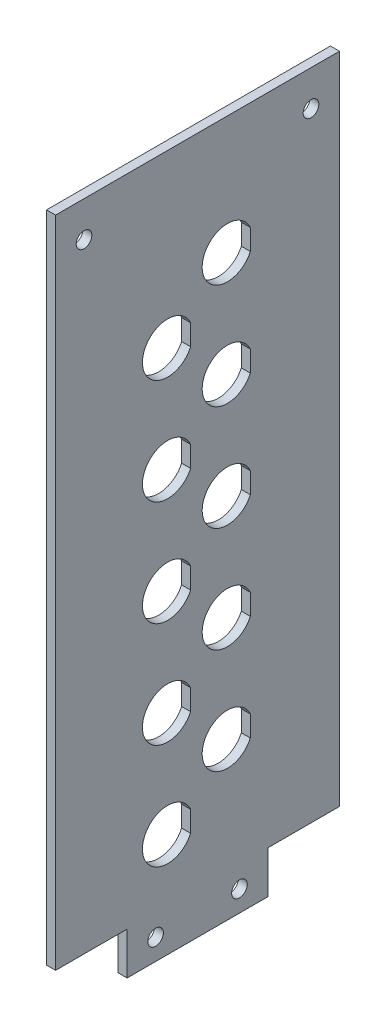
SolidWorks part; units mm, degrees
ref_plane "Front Plane" through (0, 0, 0) normal (1, 0, 0) x (0, 1, 0)
ref_plane "Top Plane" through (0, 0, 0) normal (0, 0, 1) x (0, 1, 0)
ref_plane "Right Plane" through (0, 0, 0) normal (0, 1, 0) x (-1, 0, 0)
sketch "Sketch1" plane through (0, 0, 0) normal (1, 0, 0) x (0, 1, 0)
  line L0 (-129.9, 24.75) -> (-115, 49.9) construction
  line L1 (-115, -49.9) -> (115, -49.9)
  line L2 (-115, -49.9) -> (-115, 49.9)
  line L3 (-115, 49.9) -> (115, 49.9)
  line L4 (115, -49.9) -> (115, 49.9)
  line L5 (-115, -49.9) -> (115, 49.9) construction
  line L6 (-115, 49.9) -> (115, -49.9) construction
  line L7 (-115, 24.75) -> (-129.9, 24.75)
  line L8 (-115, 24.75) -> (-115, -24.75)
  line L9 (-115, -24.75) -> (-129.9, -24.75)
  line L10 (-129.9, 24.75) -> (-129.9, -24.75)
  line L11 (-115, 24.75) -> (-129.9, -24.75) construction
  line L12 (-115, -24.75) -> (-129.9, 24.75) construction
  line L13 (-129.9, -24.75) -> (-115, -49.9) construction
  line L14 (102.5, 39.9) -> (102.5, -39.9) construction
  line L15 (102.5, 0) -> (115, 0) construction
  line L16 (-129.9, 0) -> (-122.5, 0) construction
  line L17 (-122.5, -14.75) -> (-122.5, 14.75) construction
  line L19 (-129.9, 24.75) -> (-135, 24.75) construction
  line L20 (-129.9, 24.75) -> (-129.9, -24.75) construction
  line L21 (-129.9, -24.75) -> (-135, -24.75) construction
  line L22 (-135, 24.75) -> (-135, -24.75) construction
  line L23 (-129.9, 24.75) -> (-135, -24.75) construction
  line L24 (-129.9, -24.75) -> (-135, 24.75) construction
  circle A0 centre (102.5, 39.9) radius 2.75
  circle A1 centre (102.5, -39.9) radius 2.75
  circle A2 centre (-122.5, 14.75) radius 2.75
  circle A3 centre (-122.5, -14.75) radius 2.75
  point P0 (0, 0)
  point P10 (-122.45, 0)
  point P21 (-122.5, 0)
  point P25 (-123.75, 14.75)
  point P27 (-132.45, 0)
  point P28 (-142.7036, -24.4057)
  dimension "D1" = 5.5
  dimension "D2" = 99.8
  dimension "D11" = 5.5
  dimension "D3" = 12.5
  dimension "D4" = 10
  dimension "D5" = 230
  dimension "D6" = 49.5
  dimension "D7" = 10
  dimension "D8" = 12.5
  dimension "D9" = 250
  dimension "D10" = 5.1
extrude "Boss-Extrude1" add sketch "Sketch1" along normal blind 3.175 contours L7 L10 L9 L2 A3 A2 | L1 L4 L3 L2 A1 A0
sketch "Sketch2" plane through (3.175, 0, 0) normal (1, 0, 0) x (0, 1, 0)
  line L0 (73.3412, 0) -> (73.3412, -10.5) construction
  line L1 (-115, 49.9) -> (115, 49.9) construction
  line L2 (-115, 49.9) -> (-115, -49.9) construction
  line L3 (-115, -49.9) -> (115, -49.9) construction
  line L4 (115, 49.9) -> (115, -49.9) construction
  line L5 (0, -49.9) -> (0, 49.9) construction
  line L6 (-115, 0) -> (115, 0) construction
  line L7 (-110, -24.5) -> (90, -24.5) construction
  line L8 (-110, -24.5) -> (-110, 24.5) construction
  line L9 (-110, 24.5) -> (90, 24.5) construction
  line L10 (90, -24.5) -> (90, 24.5) construction
  line L11 (-110, -24.5) -> (90, 24.5) construction
  line L12 (-110, 24.5) -> (90, -24.5) construction
  line L13 (54.8209, 0) -> (54.8209, 10.5) construction
  line L14 (-19.2601, 10.5) -> (-0.7399, -10.5) construction
  line L15 (51.1685, 2.4228) -> (58.4733, 2.4228)
  line L16 (69.6888, -18.5772) -> (76.9936, -18.5772)
  line L17 (14.128, 2.4228) -> (21.4328, 2.4228)
  line L18 (32.6483, -18.5772) -> (39.953, -18.5772)
  line L19 (-22.9125, 2.4228) -> (-15.6077, 2.4228)
  line L20 (-4.3923, -18.5772) -> (2.9125, -18.5772)
  line L21 (-59.953, 2.4228) -> (-52.6483, 2.4228)
  line L22 (-41.4328, -18.5772) -> (-34.128, -18.5772)
  line L23 (-96.9936, 2.4228) -> (-89.6888, 2.4228)
  line L24 (-78.4733, -18.5772) -> (-71.1685, -18.5772)
  line L25 (0, 0) -> (-10, 0) construction
  line L26 (115, 49.9) -> (-135, 49.9) construction
  line L27 (-110, 24.5) -> (-135, 24.5) construction
  line L28 (-135, 49.9) -> (-115, 49.9) construction
  line L29 (-135, 49.9) -> (-135, -49.9) construction
  line L30 (-135, -49.9) -> (-115, -49.9) construction
  line L31 (-115, 49.9) -> (-115, -49.9) construction
  line L32 (-135, 49.9) -> (-115, -49.9) construction
  line L33 (-135, -49.9) -> (-115, 49.9) construction
  line L34 (90, 24.5) -> (115, 24.5) construction
  circle A0 centre (73.3412, -10.5) radius 14 construction
  circle A1 centre (54.8209, 10.5) radius 14 construction
  circle A2 centre (17.7804, 10.5) radius 14 construction
  circle A3 centre (36.3006, -10.5) radius 14 construction
  circle A4 centre (-19.2601, 10.5) radius 14 construction
  circle A5 centre (-0.7399, -10.5) radius 14 construction
  circle A6 centre (-56.3006, 10.5) radius 14 construction
  circle A7 centre (-37.7804, -10.5) radius 14 construction
  circle A8 centre (-93.3412, 10.5) radius 14 construction
  circle A9 centre (-74.8209, -10.5) radius 14 construction
  circle A10 centre (73.3412, -10.5) radius 8.8646 construction
  circle A11 centre (54.8209, 10.5) radius 8.8646 construction
  arc A12 (69.6888, -18.5772) -> (76.9936, -18.5772) centre (73.3412, -10.5) cw
  arc A13 (51.1685, 2.4228) -> (58.4733, 2.4228) centre (54.8209, 10.5) cw
  arc A14 (14.128, 2.4228) -> (21.4328, 2.4228) centre (17.7804, 10.5) cw
  arc A15 (32.6483, -18.5772) -> (39.953, -18.5772) centre (36.3006, -10.5) cw
  arc A16 (-22.9125, 2.4228) -> (-15.6077, 2.4228) centre (-19.2601, 10.5) cw
  arc A17 (-4.3923, -18.5772) -> (2.9125, -18.5772) centre (-0.7399, -10.5) cw
  arc A18 (-59.953, 2.4228) -> (-52.6483, 2.4228) centre (-56.3006, 10.5) cw
  arc A19 (-41.4328, -18.5772) -> (-34.128, -18.5772) centre (-37.7804, -10.5) cw
  arc A20 (-96.9936, 2.4228) -> (-89.6888, 2.4228) centre (-93.3412, 10.5) cw
  arc A21 (-78.4733, -18.5772) -> (-71.1685, -18.5772) centre (-74.8209, -10.5) cw
  point P4 (0, 0)
  point P16 (0, 0)
  point P21 (87.3412, -10.5)
  point P38 (73.3412, -1.6354)
  point P59 (-125, 0)
  point P248 (0, 0)
  dimension "D3" = 28
  dimension "D4" = 28
  dimension "D6" = 17.7292
  dimension "D1" = 49
  dimension "D2" = 200
  dimension "D7" = 16.9418
  dimension "D9" = 250
  dimension "D5" = 5
  dimension "D8" = 5
extrude "Cut-Extrude1" cut sketch "Sketch2" against normal through all
